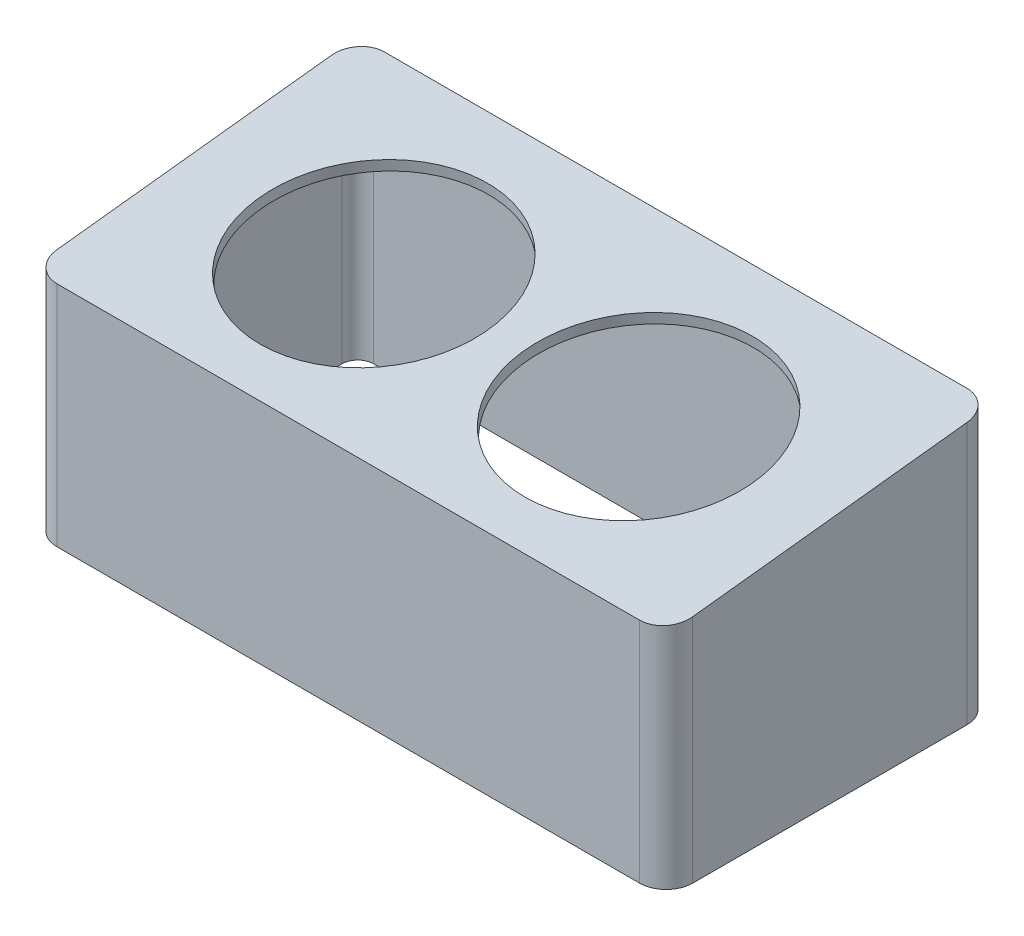
SolidWorks part; units mm, degrees
ref_plane "前视基准面" through (0, 0, 0) normal (0, 0, 1) x (1, 0, 0)
ref_plane "上视基准面" through (0, 0, 0) normal (0, 1, 0) x (1, 0, 0)
ref_plane "右视基准面" through (0, 0, 0) normal (1, 0, 0) x (0, 0, -1)
other "Configuration Table"
sketch "草图3" plane through (0, 0, 0) normal (0, 1, 0) x (1, 0, 0)
  line L1 (-35.2583, 30.485) -> (74.7417, 30.485)
  line L2 (-40.2583, 25.485) -> (-40.2583, -26.315)
  line L3 (-35.2583, -31.315) -> (74.7417, -31.315)
  line L4 (79.7417, 25.485) -> (79.7417, -26.315)
  arc A0 (-40.2583, -26.315) -> (-35.2583, -31.315) centre (-35.2583, -26.315) ccw
  arc A1 (74.7417, -31.315) -> (79.7417, -26.315) centre (74.7417, -26.315) ccw
  arc A2 (74.7417, 30.485) -> (79.7417, 25.485) centre (74.7417, 25.485) cw
  arc A3 (-35.2583, 30.485) -> (-40.2583, 25.485) centre (-35.2583, 25.485) ccw
  point P6 (-40.2583, -31.315)
  point P11 (79.7417, 30.485)
  point P14 (-40.2583, 30.485)
  dimension "D3" = 5
  dimension "D1" = 61.8
  dimension "D2" = 120
extrude "凸台-拉伸6" add sketch "草图3" along normal blind 50 contours A3 L2 A0 L3 A1 L4 A2 L1
sketch "草图4" plane through (79.7417, 0, 0) normal (1, 0, 0) x (0, 0, -1)
  line L0 (30.485, 50) -> (-31.315, 43)
  line L1 (-31.315, 50) -> (-31.315, 0) construction
  line L2 (-31.315, 43) -> (-31.315, 50)
  line L3 (-31.315, 50) -> (30.485, 50)
  dimension "D1" = 7
extrude "切除-拉伸1" cut sketch "草图4" against normal through all both and the other way through all contours L3 L0 L2
sketch "草图5" plane through (0, 45.9574, 5.2055) normal (0, 0.9936, 0.1125) x (1, 0, 0)
  line L0 (19.7417, -26.2764) -> (19.7417, 35.9188) construction
  line L1 (-35.2583, -26.2764) -> (74.7417, -26.2764) construction
  line L2 (-35.2583, 35.9188) -> (74.7417, 35.9188) construction
  circle A0 centre (44.7417, 3.7236) radius 21.6018
  circle A1 centre (-5.2583, 3.7236) radius 21.6018
  dimension "D1" = 50
  dimension "D2" = 30
extrude "切除-拉伸2" cut sketch "草图5" against normal through all contours A1 | A0
sketch "草图7" plane through (0, 0, 0) normal (0, -1, 0) x (-1, 0, 0)
  line L1 (33.2583, -29.315) -> (-72.7417, -29.315)
  line L2 (38.2583, -24.315) -> (38.2583, 23.485)
  line L3 (33.2583, 28.485) -> (-72.7417, 28.485)
  line L4 (-77.7417, -24.315) -> (-77.7417, 23.485)
  line L5 (35.2583, -31.315) -> (-74.7417, -31.315) construction
  line L6 (35.2583, 30.485) -> (-74.7417, 30.485) construction
  line L7 (40.2583, 25.485) -> (40.2583, -26.315) construction
  line L8 (-79.7417, 25.485) -> (-79.7417, -26.315) construction
  arc A1 (38.2583, 23.485) -> (33.2583, 28.485) centre (33.2583, 23.485) ccw
  arc A2 (-72.7417, 28.485) -> (-77.7417, 23.485) centre (-72.7417, 23.485) ccw
  arc A3 (-72.7417, -29.315) -> (-77.7417, -24.315) centre (-72.7417, -24.315) cw
  arc A4 (33.2583, -29.315) -> (38.2583, -24.315) centre (33.2583, -24.315) ccw
  point P14 (38.2583, 28.485)
  point P19 (-77.7417, -29.315)
  point P22 (38.2583, -29.315)
  dimension "D7" = 5
  dimension "D1" = 116
  dimension "D2" = 57.8
  dimension "D3" = 2
  dimension "D4" = 2
  dimension "D5" = 2
  dimension "D6" = 2
shell "抽壳3" thickness 2
